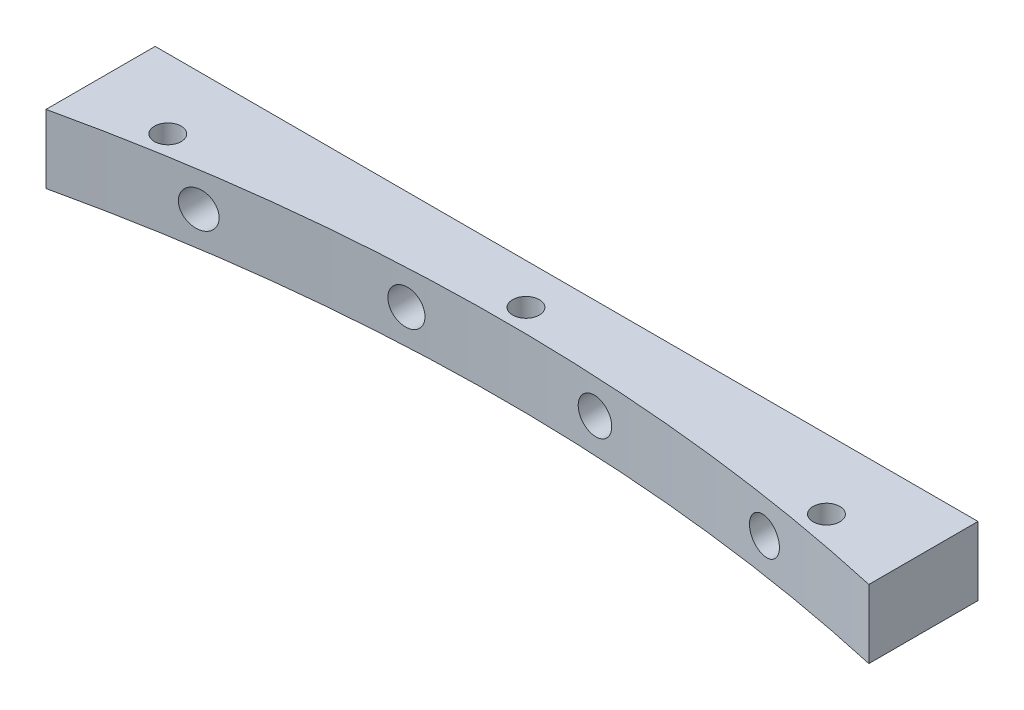
SolidWorks part; units mm, degrees
material "6061-T6 (SS)"
ref_plane "Front" through (0, 0, 0) normal (0, 0, 1) x (1, 0, 0)
ref_plane "Top" through (0, 0, 0) normal (0, 1, 0) x (1, 0, 0)
ref_plane "Right" through (0, 0, 0) normal (1, 0, 0) x (0, 0, -1)
sketch "Sketch1" plane through (0, 0, 0) normal (0, 1, 0) x (1, 0, 0)
  line L0 (-152.4, 677.1164) -> (-152.4, 717.55)
  line L1 (-152.4, 717.55) -> (152.4, 717.55)
  line L2 (152.4, 717.55) -> (152.4, 677.1164)
  line L3 (0, 0) -> (0, 944.5739) construction
  arc A0 (152.4, 677.1164) -> (-152.4, 677.1164) centre (0, 0) ccw
  dimension "D1" = 694.055
  dimension "D2" = 152.4
  dimension "D3" = 152.4
  dimension "D4" = 717.55
extrude "Boss-Extrude1" add sketch "Sketch1" along normal blind 25.4
hole_wizard "25/64 (0.39063) Diameter Hole1" positions "Sketch2" profile "Sketch3" hole size "25/64" standard "ANSI Inch" end condition through all
sketch "Sketch2" plane through (0, 25.4, 0) normal (0, 1, 0) x (1, 0, 0)
  line L0 (152.4, 677.1164) -> (152.4, 717.55) construction
  arc A0 (152.4, 677.1164) -> (-152.4, 677.1164) centre (0, 0) ccw construction
  point P0 (0, 702.5)
  dimension "D1" = 702.5
  dimension "D2" = 152.4
sketch "Sketch3" plane through (0, 25.4, -702.5) normal (1, 0, 0) x (0, 0, 1)
  line L0 (0, 0) -> (0, 25.4)
  line L1 (0, 25.4) -> (4.961, 25.4)
  line L2 (4.961, 25.4) -> (4.961, 0)
  line L5 (4.961, 0) -> (0, 0)
  line L11 (0, -6.35) -> (0, 107.95) construction
  dimension "Thru Hole Dia." = 9.922
  dimension "Thru Hole Depth" = 25.4
pattern_circular "CirPattern4" count 36 over 360 about axis through (0, 0, 0) along (0, 1, 0) skipping 2, 3, 4, 5, 6, 7, 8, 9, 10, 11, 12, 13, 14, 15, 16, 17, 18, 19, 20, 21, 22, 23, 24, 25, 26, 27, 28, 29, 30, 31, 32, 33, 34 of "25/64 (0.39063) Diameter Hole1"
hole_wizard "Tapped Hole for 1/2-13 Helicoil1" positions "Sketch4" profile "Sketch5" tap size "1/2-13" standard "Helicoil® Inch" end condition through all
sketch "Sketch4" plane through (0, 0, -717.55) normal (0, 0, -1) x (-1, 0, 0)
  line L0 (-152.4, 25.4) -> (152.4, 25.4) construction
  line L1 (-152.4, 25.4) -> (-152.4, 0) construction
  point P0 (-104.775, 12.7)
  dimension "D1" = 12.7
  dimension "D2" = 47.625
sketch "Sketch5" plane through (104.775, 12.7, -717.55) normal (1, 0, 0) x (0, 1, 0)
  line L0 (0, 0) -> (0, 40.4336)
  line L1 (0, 40.4336) -> (6.5481, 40.4336)
  line L2 (6.5481, 40.4336) -> (6.5481, 0)
  line L5 (6.5481, 0) -> (0, 0)
  line L11 (0, -6.35) -> (0, 107.95) construction
  dimension "Thru Tap Drill Dia." = 13.0962
  dimension "Thru Tap Drill Depth" = 40.4336
cosmetic thread "Hole Thread1" parameters "D1"=14.732, "D2"=15.3467
pattern_linear "LPattern1" count 4 spacing 69.85 along (-1, 0, 0) of "Tapped Hole for 1/2-13 Helicoil1"
cosmetic thread "Hole Thread2" parameters "D1"=14.732, "D2"=15.3467
cosmetic thread "Hole Thread3" parameters "D1"=14.732, "D2"=15.3467
cosmetic thread "Hole Thread4" parameters "D1"=14.732, "D2"=15.3467
